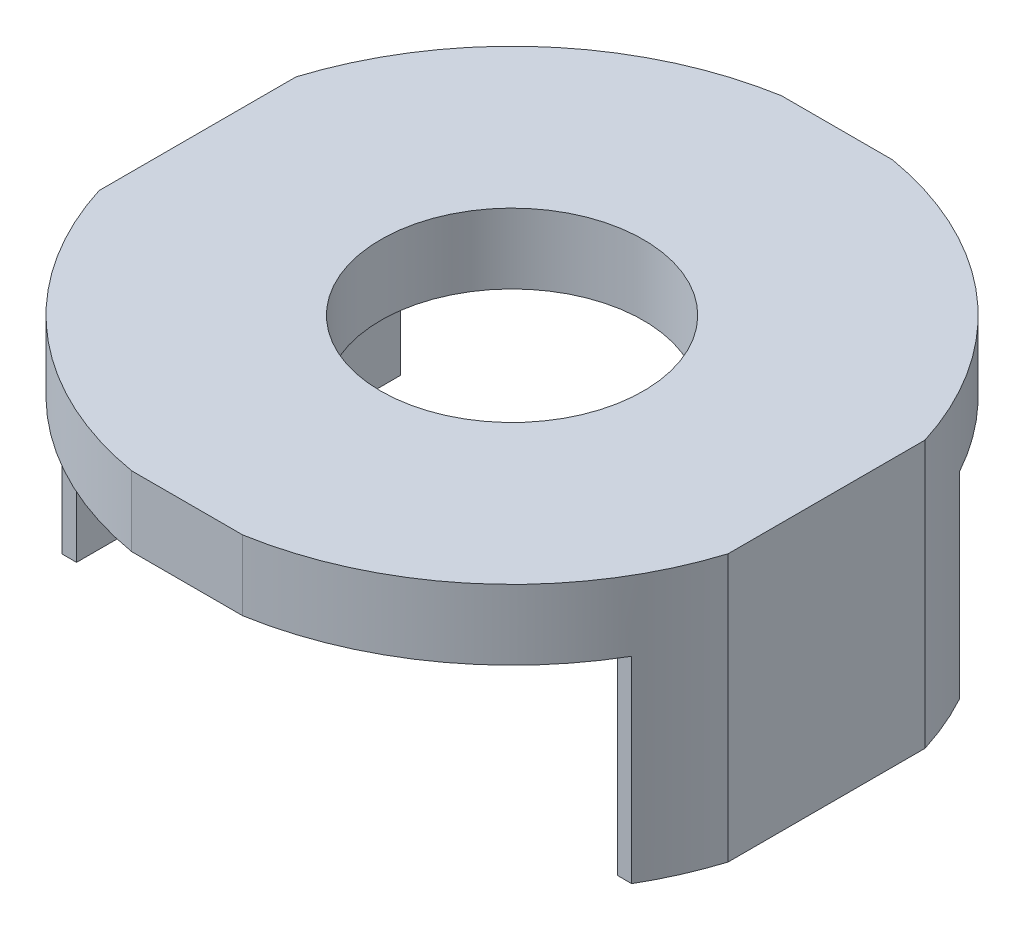
SolidWorks part; units mm, degrees
ref_plane "Front Plane" through (0, 0, 0) normal (0, 0, 1) x (1, 0, 0)
ref_plane "Top Plane" through (0, 0, 0) normal (0, 1, 0) x (1, 0, 0)
ref_plane "Right Plane" through (0, 0, 0) normal (1, 0, 0) x (0, 0, -1)
sketch "Sketch1" plane through (0, 0, 0) normal (0, 1, 0) x (1, 0, 0)
  line L0 (1.2682, -7.4224) -> (-1.2682, -7.4224)
  line L1 (-1.2682, 7.4224) -> (1.2682, 7.4224)
  line L6 (-7.186, -2.25) -> (-7.186, 2.25)
  line L7 (7.186, -2.25) -> (7.186, 2.25)
  circle A0 centre (0, 0) radius 3
  arc A5 (1.2682, -7.4224) -> (7.186, -2.25) centre (0, 0) ccw
  arc A6 (-1.2682, 7.4224) -> (-7.186, 2.25) centre (0, 0) ccw
  arc A7 (-7.186, -2.25) -> (-1.2682, -7.4224) centre (0, 0) ccw
  arc A8 (7.186, 2.25) -> (1.2682, 7.4224) centre (0, 0) ccw
  point P7 (0, 0)
  point P10 (0, 7.475)
  point P15 (-6.5, 0)
  point P17 (-7.186, 0)
  point P19 (6.5, 0)
  point P21 (7.186, 0)
  dimension "D1" = 2
  dimension "D3" = 6
  dimension "D2" = 7.53
  dimension "D4" = 4.5
  dimension "D5" = 4.5
extrude "Boss-Extrude1" add sketch "Sketch1" along normal blind 1.6
sketch "Sketch2" plane through (0, 0, 0) normal (0, -1, 0) x (1, 0, 0)
  line L1 (-7.186, -3.6358) -> (-6.186, -3.6358)
  line L6 (6.186, -3.62) -> (7.186, -3.62)
  line L7 (6.186, -3.62) -> (6.186, 3.78)
  line L8 (-7.186, -3.6358) -> (-7.186, 3.7642)
  line L9 (-7.186, 3.7642) -> (-6.186, 3.7642)
  line L10 (-6.186, -3.6358) -> (-6.186, 3.7642)
  line L11 (-7.186, -3.6358) -> (-6.186, 3.7642) construction
  line L12 (-7.186, 3.7642) -> (-6.186, -3.6358) construction
  line L14 (6.186, 3.78) -> (7.186, 3.78)
  line L15 (7.186, -3.62) -> (7.186, 3.78)
  line L16 (6.186, -3.62) -> (7.186, 3.78) construction
  line L17 (6.186, 3.78) -> (7.186, -3.62) construction
  line L18 (-7.186, -2.25) -> (-7.186, 2.25) construction
  line L19 (7.186, 2.25) -> (7.186, -2.25) construction
  point P4 (0, 0)
  dimension "D1" = 1
  dimension "D2" = 1
  dimension "D3" = 1
extrude "Boss-Extrude3" add sketch "Sketch2" along normal blind 4.5
